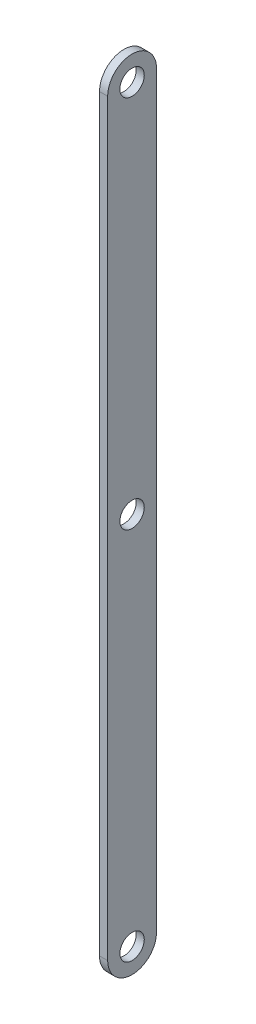
SolidWorks part; units mm, degrees
ref_plane "Front Plane" through (0, 0, 0) normal (1, 0, 0) x (0, 1, 0)
ref_plane "Top Plane" through (0, 0, 0) normal (0, 0, 1) x (0, 1, 0)
ref_plane "Right Plane" through (0, 0, 0) normal (0, 1, 0) x (-1, 0, 0)
sketch "Sketch1" plane through (0, 0, 0) normal (1, 0, 0) x (0, 1, 0)
  line L0 (-230, 0) -> (230, 0) construction
  line L1 (-230, 0) -> (230, 0) construction
  line L2 (-230, 15) -> (230, 15)
  line L3 (-230, -15) -> (230, -15)
  arc A0 (-230, 15) -> (-230, -15) centre (-230, 0) ccw
  arc A1 (230, -15) -> (230, 15) centre (230, 0) ccw
  circle A2 centre (-230, 0) radius 7.5
  circle A3 centre (0, 0) radius 7.5
  circle A4 centre (230, 0) radius 7.5
  point P4 (0, 0)
  dimension "D2" = 15
  dimension "D3" = 15
  dimension "D4" = 15
  dimension "D5" = 15
  dimension "D1" = 460
extrude "Boss-Extrude1" add sketch "Sketch1" against normal blind 5
